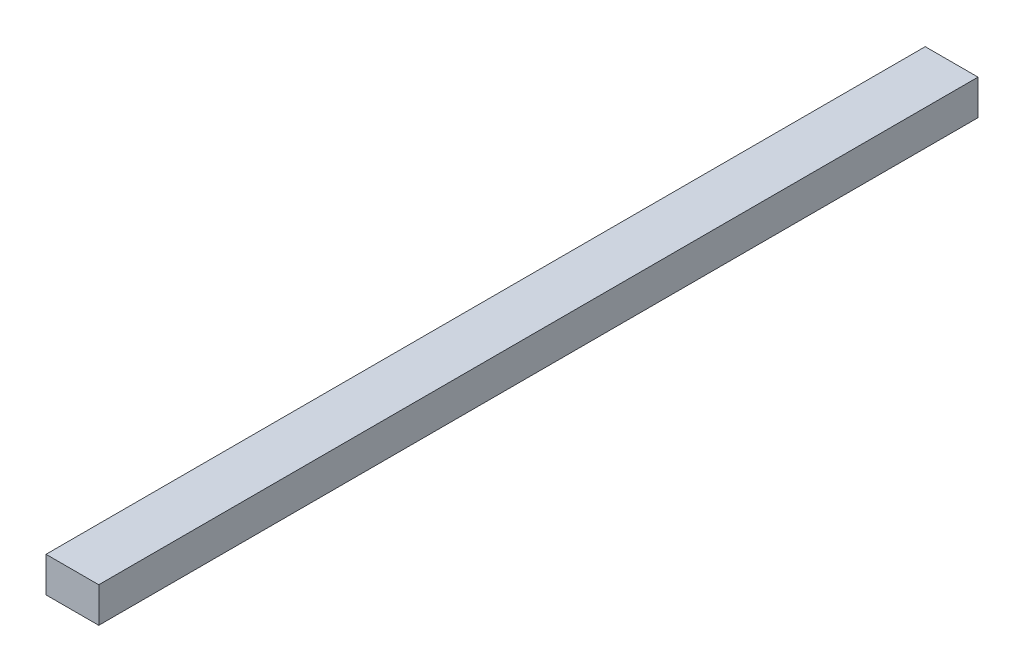
SolidWorks part; units mm, degrees
ref_plane "Front" through (0, 0, 0) normal (0, 0, 1) x (1, 0, 0)
ref_plane "Top" through (0, 0, 0) normal (0, 1, 0) x (1, 0, 0)
ref_plane "Right" through (0, 0, 0) normal (1, 0, 0) x (0, 0, -1)
sketch "Sketch1" plane through (0, 0, 0) normal (0, 0, 1) x (1, 0, 0)
  line L1 (-11.1196, 6.9677) -> (18.8804, 6.9677)
  line L2 (-11.1196, 6.9677) -> (-11.1196, -13.0323)
  line L3 (-11.1196, -13.0323) -> (18.8804, -13.0323)
  line L4 (18.8804, 6.9677) -> (18.8804, -13.0323)
  dimension "D1" = 30
  dimension "D2" = 20
extrude "Boss-Extrude1" add sketch "Sketch1" along normal blind 500
